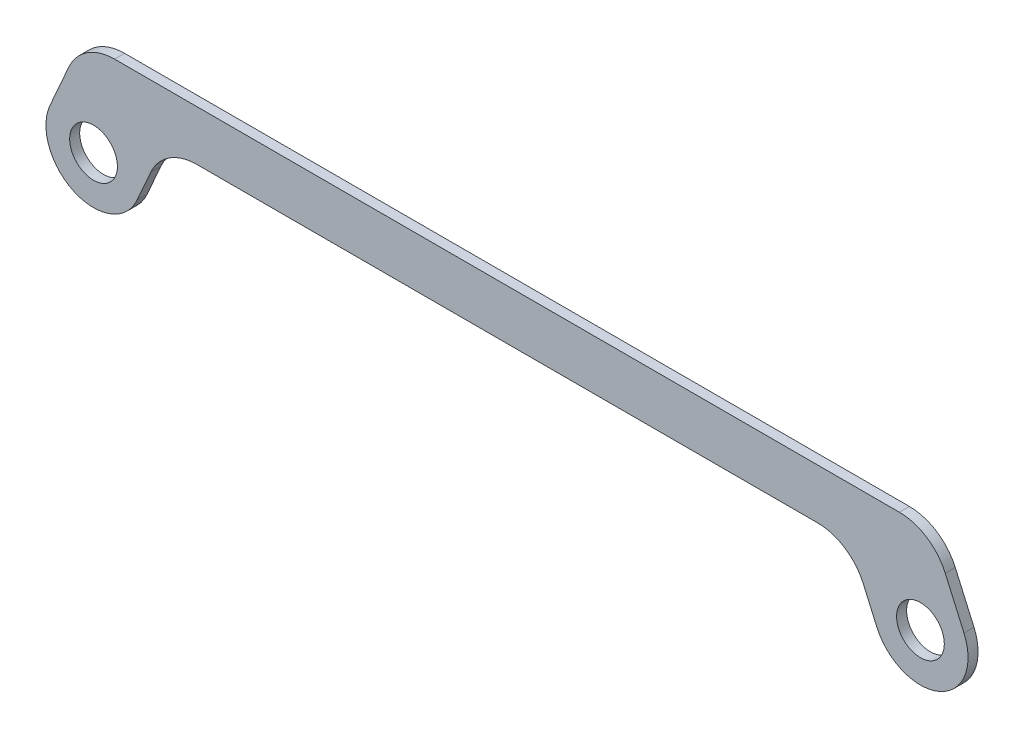
SolidWorks part; units mm, degrees
ref_plane "前视基准面" through (0, 0, 0) normal (0, 0, 1) x (1, 0, 0)
ref_plane "上视基准面" through (0, 0, 0) normal (0, 1, 0) x (1, 0, 0)
ref_plane "右视基准面" through (0, 0, 0) normal (1, 0, 0) x (0, 0, -1)
sketch "草图1" plane through (0, 0, 0) normal (0, 0, 1) x (1, 0, 0)
  line L28 (0, 0) -> (330, 0) construction
  line L31 (-4.6396, 36.5501) -> (334.6396, 36.5501)
  line L32 (28.0703, 16.5501) -> (301.9297, 16.5501)
  line L33 (17.3829, -7.6703) -> (28.0703, 16.5501)
  line L34 (-17.3829, 7.6703) -> (-4.6396, 36.5501)
  line L35 (165, 0) -> (165, -17.6097) construction
  line L36 (312.6171, -7.6703) -> (301.9297, 16.5501)
  line L37 (347.3829, 7.6703) -> (334.6396, 36.5501)
  circle A24 centre (0, 0) radius 19 construction
  circle A25 centre (0, 0) radius 9.525
  circle A26 centre (330, 0) radius 9.525
  circle A27 centre (330, 0) radius 19 construction
  arc A30 (17.3829, -7.6703) -> (-17.3829, 7.6703) centre (0, 0) cw
  arc A31 (312.6171, -7.6703) -> (347.3829, 7.6703) centre (330, 0) ccw
  dimension "D1" = 19.05
  dimension "D3" = 330
  dimension "D4" = 20
  dimension "D2" = 38
extrude "凸台-拉伸1" add sketch "草图1" along normal blind 4
fillet "圆角1" radius 20 4 edges at (301.9297, 16.5501, 2) (334.6396, 36.5501, 2) (28.0703, 16.5501, 2) (-4.6396, 36.5501, 2)
